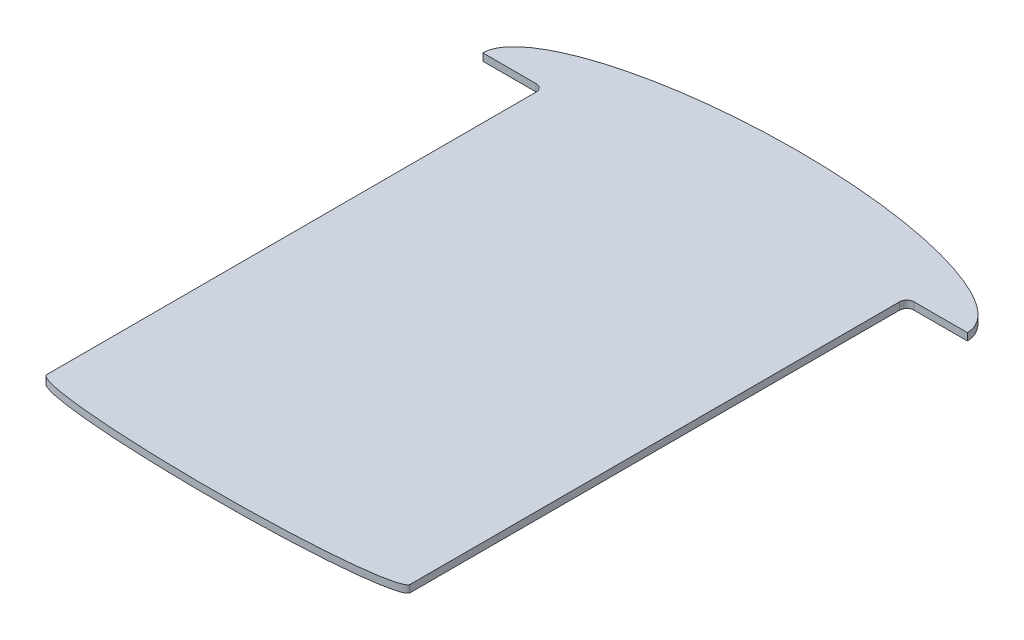
SolidWorks part; units mm, degrees
ref_plane "Front Plane" through (0, 0, 0) normal (0, 0, 1) x (1, 0, 0)
ref_plane "Top Plane" through (0, 0, 0) normal (0, 1, 0) x (1, 0, 0)
ref_plane "Right Plane" through (0, 0, 0) normal (1, 0, 0) x (0, 0, -1)
sketch "Sketch1" plane through (0, 0, 0) normal (0, 1, 0) x (1, 0, 0)
  line L0 (-75, 80) -> (75, 80) construction
  line L2 (-75, 95) -> (-75, -110)
  line L4 (75, 95) -> (75, -110)
  line L5 (-75, 110) -> (75, -110) construction
  line L6 (-75, -110) -> (64.7727, 95) construction
  line L7 (-75, 80) -> (75, 110) construction
  line L8 (75, 80) -> (-75, 110) construction
  line L9 (-100, 95) -> (-75, 95)
  line L11 (75, 95) -> (100, 95)
  ellipse E0 centre (0, 95) end of major axis (100, 95) minor radius 30 (100, 95) -> (-100, 95) ccw
  ellipse E1 centre (0, -110) end of major axis (75, -110) minor radius 7.011 (-74.3931, -109.1099) -> (74.3931, -109.1099) ccw
  point P0 (0, 0)
  dimension "D1" = 220
  dimension "D2" = 150
extrude "Boss-Extrude1" add sketch "Sketch1" along normal blind 3
fillet "Fillet1" radius 3 2 edges at (75, 1.5, -95) (-75, 1.5, -95)
sketch "Sketch2" plane through (0, 3, 0) normal (0, 1, 0) x (1, 0, 0)
  line L0 (-75, -110) -> (75, -110) construction
  point P0 (0, -110)
  point P1 (0, -119.3317)
